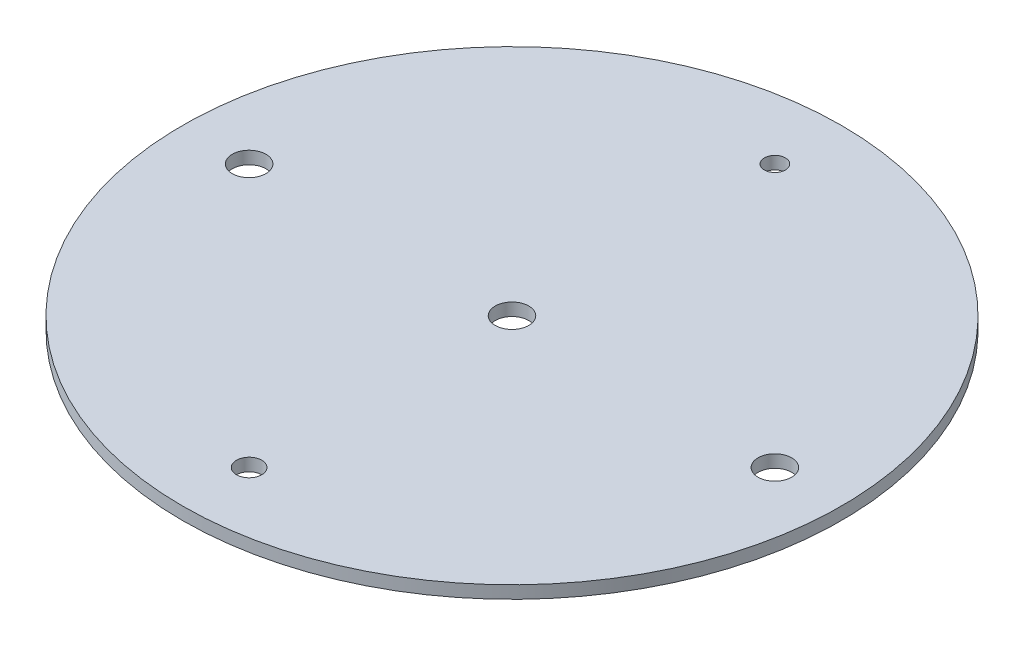
SolidWorks part; units mm, degrees
material "1060 Alloy"
ref_plane "Front Plane" through (0, 0, 0) normal (0, 0, 1) x (1, 0, 0)
ref_plane "Top Plane" through (0, 0, 0) normal (0, 1, 0) x (1, 0, 0)
ref_plane "Right Plane" through (0, 0, 0) normal (1, 0, 0) x (0, 0, -1)
sketch "Sketch1" plane through (0, 0, 0) normal (0, 1, 0) x (1, 0, 0)
  circle A0 centre (0, 0) radius 78.35
  circle A1 centre (-62.5, 0) radius 4
  circle A2 centre (0, 0) radius 62.5 construction
  circle A3 centre (0, -62.5) radius 3
  circle A4 centre (0, 62.5) radius 2.5
  circle A5 centre (62.5, 0) radius 4
  circle A6 centre (0, 0) radius 4
  dimension "D1" = 156.7
  dimension "D2" = 125
  dimension "D3" = 8
  dimension "D4" = 8
  dimension "D5" = 5
  dimension "D6" = 6
  dimension "D7" = 8
extrude "Boss-Extrude1" add sketch "Sketch1" along normal blind 3
